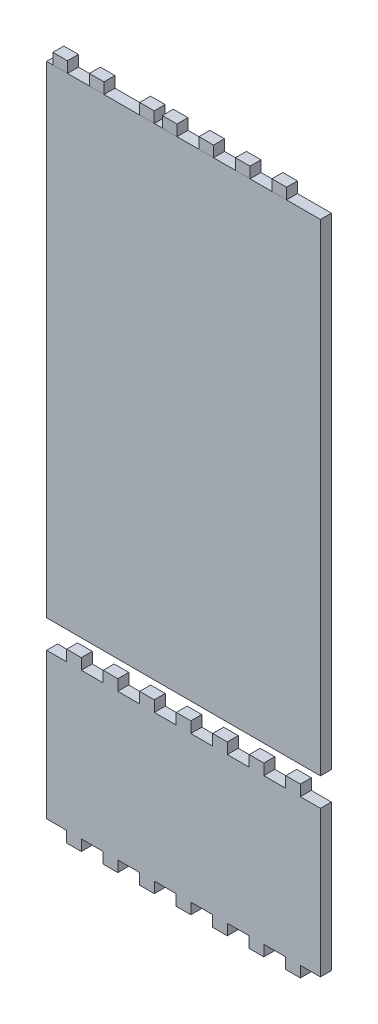
SolidWorks part; units mm, degrees
ref_plane "Plan de face" through (0, 0, 0) normal (0, 0, 1) x (1, 0, 0)
ref_plane "Plan de dessus" through (0, 0, 0) normal (0, 1, 0) x (1, 0, 0)
ref_plane "Plan de droite" through (0, 0, 0) normal (1, 0, 0) x (0, 0, -1)
sketch "Esquisse1" plane through (0, 0, 0) normal (0, 0, 1) x (1, 0, 0)
  line L0 (0, -86) -> (150, -86)
  line L1 (0, 0) -> (150, 0)
  line L2 (0, 0) -> (0, -80)
  line L3 (0, -80) -> (150, -80)
  line L4 (150, 0) -> (150, -80)
  line L5 (0, -80) -> (11, -80)
  line L6 (0, -80) -> (0, -86)
  line L7 (0, -86) -> (11, -86)
  line L8 (11, -80) -> (11, -86)
  line L9 (11, -86) -> (19, -86)
  line L10 (11, -86) -> (11, -80)
  line L11 (11, -80) -> (19, -80)
  line L12 (19, -86) -> (19, -80)
  line L13 (39, -86) -> (39, -80)
  line L14 (31, -86) -> (39, -86)
  line L15 (31, -80) -> (31, -86)
  line L16 (20, -86) -> (31, -86)
  line L17 (0, -40) -> (150, -40) construction
  line L18 (59, -86) -> (59, -80)
  line L19 (51, -86) -> (59, -86)
  line L20 (51, -80) -> (51, -86)
  line L21 (40, -86) -> (51, -86)
  line L22 (120, 6) -> (131, 6)
  line L23 (79, -86) -> (79, -80)
  line L24 (71, -86) -> (79, -86)
  line L25 (71, -80) -> (71, -86)
  line L26 (60, -86) -> (71, -86)
  line L27 (131, 0) -> (131, 6)
  line L28 (99, -86) -> (99, -80)
  line L29 (91, -86) -> (99, -86)
  line L30 (91, -80) -> (91, -86)
  line L31 (80, -86) -> (91, -86)
  line L32 (131, 6) -> (139, 6)
  line L33 (119, -86) -> (119, -80)
  line L34 (111, -86) -> (119, -86)
  line L35 (111, -80) -> (111, -86)
  line L36 (100, -86) -> (111, -86)
  line L37 (139, 6) -> (139, 0)
  line L38 (139, -86) -> (139, -80)
  line L39 (131, -86) -> (139, -86)
  line L40 (131, -80) -> (131, -86)
  line L41 (120, -86) -> (131, -86)
  line L42 (170, 0) -> (170, -80) [skipped]
  line L43 (190, 0) -> (190, -80) [skipped]
  line L44 (210, 0) -> (210, -80) [skipped]
  line L45 (230, 0) -> (230, -80) [skipped]
  line L46 (250, 0) -> (250, -80) [skipped]
  line L47 (270, 0) -> (270, -80) [skipped]
  line L48 (100, 6) -> (111, 6)
  line L49 (111, 0) -> (111, 6)
  line L50 (111, 6) -> (119, 6)
  line L51 (119, 6) -> (119, 0)
  line L52 (80, 6) -> (91, 6)
  line L53 (91, 0) -> (91, 6)
  line L54 (91, 6) -> (99, 6)
  line L55 (99, 6) -> (99, 0)
  line L56 (60, 6) -> (71, 6)
  line L57 (71, 0) -> (71, 6)
  line L58 (71, 6) -> (79, 6)
  line L59 (79, 6) -> (79, 0)
  line L60 (40, 6) -> (51, 6)
  line L61 (51, 0) -> (51, 6)
  line L62 (51, 6) -> (59, 6)
  line L63 (59, 6) -> (59, 0)
  line L64 (20, 6) -> (31, 6)
  line L65 (31, 0) -> (31, 6)
  line L66 (31, 6) -> (39, 6)
  line L67 (39, 6) -> (39, 0)
  line L68 (19, 6) -> (19, 0)
  line L69 (11, 0) -> (19, 0)
  line L70 (11, 6) -> (11, 0)
  line L71 (11, 6) -> (19, 6)
  line L72 (11, 0) -> (11, 6)
  line L73 (0, 6) -> (11, 6)
  line L74 (0, 0) -> (0, 6)
  line L75 (0, 0) -> (11, 0)
  line L76 (0, 0) -> (150, 0)
  line L77 (0, 6) -> (150, 6)
  dimension "D1" = 80
  dimension "D2" = 150
  dimension "D3" = 6
  dimension "D4" = 11
  dimension "D5" = 8
  dimension "D6" = 7
extrude "Boss.-Extru.1" add sketch "Esquisse1" along normal blind 6 contours L17 L2 L73 L71 L77 L64 L66 L60 L62 L56 L58 L52 L54 L48 L50 L22 L32 L4 | L2 L17 L4 L0 | L0 L12 L3 L8 | L3 L15 L0 L13 | L3 L20 L0 L18 | L3 L25 L0 L23 | L3 L30 L0 L28 | L3 L35 L0 L33 | L3 L40 L0 L38 | L37 L32 L27 L1 | L51 L50 L49 L1 | L55 L54 L53 L1 | L59 L58 L57 L1 | L63 L62 L61 L1 | L67 L66 L65 L1 | L71 L70 L1 L68
sketch "Esquisse4" plane through (0, 0, 6) normal (0, 0, 1) x (1, 0, 0)
  line L0 (177.4331, 15.3754) -> (131.4331, 15.3754) construction
  line L1 (150, 15.3754) -> (0, 15.3754)
  line L2 (150, 15.3754) -> (150, 279.3754)
  line L3 (150, 279.3754) -> (0, 279.3754)
  line L4 (0, 15.3754) -> (0, 279.3754)
  line L5 (177.4331, 279.3754) -> (131.4331, 279.3754) construction
  line L6 (150, -80) -> (150, 0) construction
  line L7 (0, -80) -> (0, 0) construction
extrude "Boss.-Extru.2" add sketch "Esquisse4" against normal blind 6
sketch "Esquisse5" plane through (0, 0, 6) normal (0, 0, 1) x (1, 0, 0)
  line L0 (150, 279.3754) -> (0, 279.3754) construction
  line L1 (3.4331, 279.3754) -> (11.4331, 279.3754)
  line L2 (3.4331, 279.3754) -> (3.4331, 285.3754)
  line L3 (3.4331, 285.3754) -> (11.4331, 285.3754)
  line L4 (11.4331, 279.3754) -> (11.4331, 285.3754)
  line L5 (3.4331, 279.3754) -> (3.4331, 285.3754) construction
  line L6 (23.4331, 279.3754) -> (23.4331, 285.3754) construction
  line L7 (23.4331, 279.3754) -> (31.4331, 279.3754)
  line L8 (23.4331, 279.3754) -> (23.4331, 285.3754)
  line L9 (23.4331, 285.3754) -> (31.4331, 285.3754)
  line L10 (31.4331, 279.3754) -> (31.4331, 285.3754)
  line L11 (63.4331, 279.3754) -> (63.4331, 285.3754) construction
  line L12 (50.9629, 279.3754) -> (58.9629, 279.3754)
  line L13 (50.9629, 279.3754) -> (50.9629, 285.3754)
  line L14 (50.9629, 285.3754) -> (58.9629, 285.3754)
  line L15 (58.9629, 279.3754) -> (58.9629, 285.3754)
  line L16 (63.4331, 279.3754) -> (71.4331, 279.3754)
  line L17 (63.4331, 279.3754) -> (63.4331, 285.3754)
  line L18 (63.4331, 285.3754) -> (71.4331, 285.3754)
  line L19 (71.4331, 279.3754) -> (71.4331, 285.3754)
  line L20 (83.4331, 279.3754) -> (83.4331, 285.3754) construction
  line L21 (83.4331, 279.3754) -> (91.4331, 279.3754)
  line L22 (83.4331, 279.3754) -> (83.4331, 285.3754)
  line L23 (83.4331, 285.3754) -> (91.4331, 285.3754)
  line L24 (91.4331, 279.3754) -> (91.4331, 285.3754)
  line L25 (103.4331, 279.3754) -> (103.4331, 285.3754) construction
  line L26 (103.4331, 279.3754) -> (111.4331, 279.3754)
  line L27 (103.4331, 279.3754) -> (103.4331, 285.3754)
  line L28 (103.4331, 285.3754) -> (111.4331, 285.3754)
  line L29 (111.4331, 279.3754) -> (111.4331, 285.3754)
  line L30 (123.4331, 279.3754) -> (123.4331, 285.3754) construction
  line L31 (123.4331, 279.3754) -> (131.4331, 279.3754)
  line L32 (123.4331, 279.3754) -> (123.4331, 285.3754)
  line L33 (123.4331, 285.3754) -> (131.4331, 285.3754)
  line L34 (131.4331, 279.3754) -> (131.4331, 285.3754)
  line L35 (359.9982, 285.3754) -> (-16.8881, 285.3754) construction
  dimension "D1" = 8
extrude "Boss.-Extru.3" add sketch "Esquisse5" against normal blind 6
